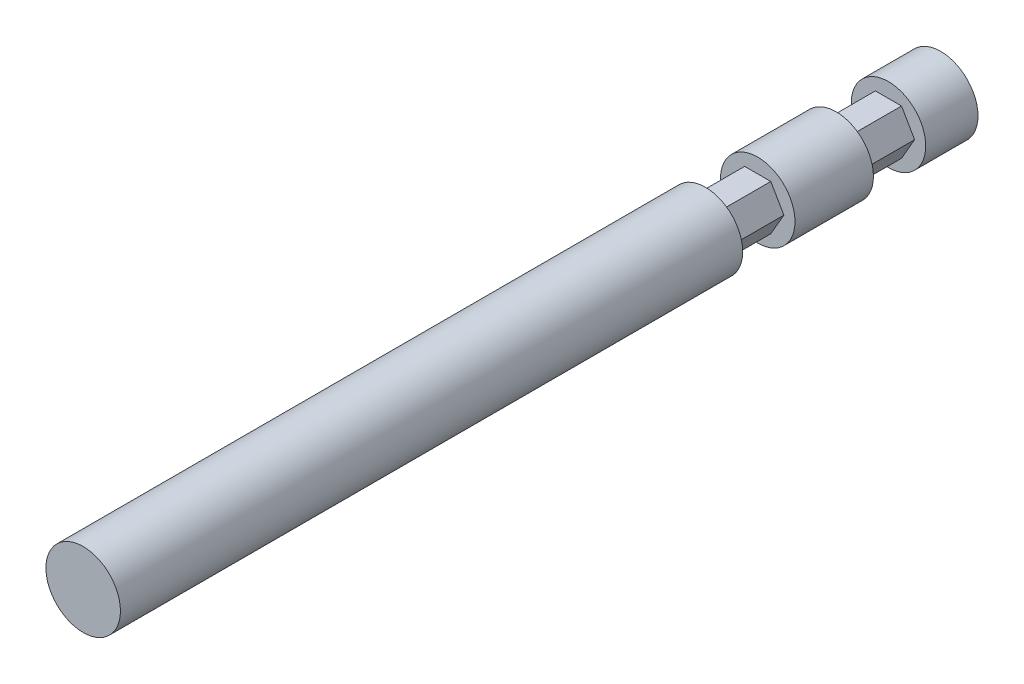
SolidWorks part; units mm, degrees
ref_plane "前视基准面" through (0, 0, 0) normal (0, 0, 1) x (1, 0, 0)
ref_plane "上视基准面" through (0, 0, 0) normal (0, 1, 0) x (1, 0, 0)
ref_plane "右视基准面" through (0, 0, 0) normal (1, 0, 0) x (0, 0, -1)
sketch "草图1" plane through (0, 0, 0) normal (0, 0, 1) x (1, 0, 0)
  circle A0 centre (0, 0) radius 2.85
  dimension "D1" = 5.7
extrude "凸台-拉伸1" add sketch "草图1" along normal blind 4
sketch "草图2" plane through (0, 0, 4) normal (0, 0, 1) x (1, 0, 0)
  line L1 (2, 0) -> (1, 1.7321)
  line L2 (1, 1.7321) -> (-1, 1.7321)
  line L3 (-1, 1.7321) -> (-2, 0)
  line L4 (-2, 0) -> (-1, -1.7321)
  line L5 (-1, -1.7321) -> (1, -1.7321)
  line L6 (1, -1.7321) -> (2, 0)
  circle A0 centre (0, 0) radius 2 construction
  dimension "D1" = 4
extrude "凸台-拉伸2" add sketch "草图2" along normal blind 4
sketch "草图3" plane through (0, 0, 8) normal (0, 0, 1) x (1, 0, 0)
  circle A0 centre (0, 0) radius 2.85
  dimension "D1" = 5.7
extrude "凸台-拉伸3" add sketch "草图3" along normal blind 6
sketch "草图4" plane through (0, 0, 14) normal (0, 0, 1) x (1, 0, 0)
  line L1 (2, 0) -> (1, 1.7321)
  line L2 (1, 1.7321) -> (-1, 1.7321)
  line L3 (-1, 1.7321) -> (-2, 0)
  line L4 (-2, 0) -> (-1, -1.7321)
  line L5 (-1, -1.7321) -> (1, -1.7321)
  line L6 (1, -1.7321) -> (2, 0)
  circle A0 centre (0, 0) radius 2 construction
  dimension "D1" = 4
extrude "凸台-拉伸4" add sketch "草图4" along normal blind 4
sketch "草图5" plane through (0, 0, 18) normal (0, 0, 1) x (1, 0, 0)
  circle A0 centre (0, 0) radius 2.85
  dimension "D1" = 5.7
extrude "凸台-拉伸5" add sketch "草图5" along normal blind 47.6
